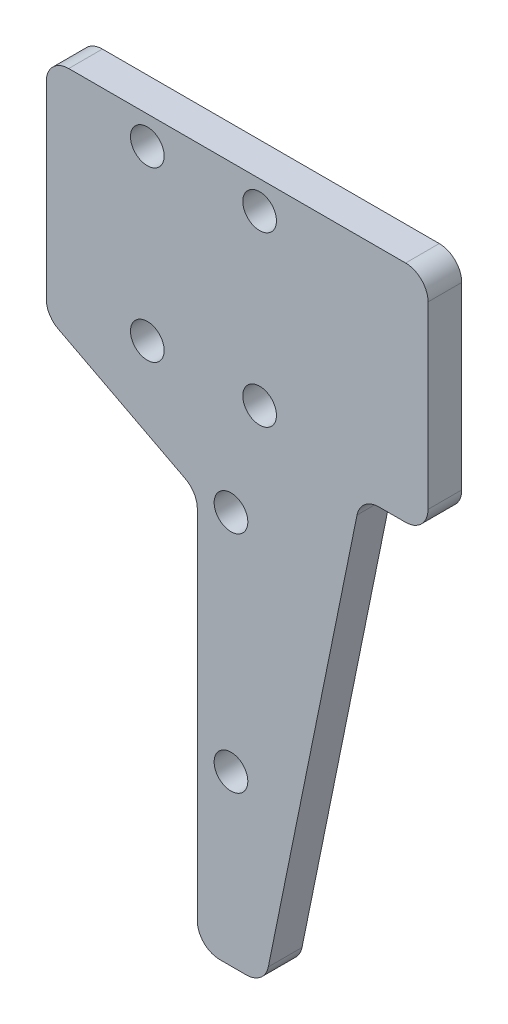
SolidWorks part; units mm, degrees
material "6061-T4 (SS)"
ref_plane "前视基准面" through (0, 0, 0) normal (0, 0, 1) x (1, 0, 0)
ref_plane "上视基准面" through (0, 0, 0) normal (0, 1, 0) x (1, 0, 0)
ref_plane "右视基准面" through (0, 0, 0) normal (1, 0, 0) x (0, 0, -1)
other "Configuration Table"
sketch "草图1" plane through (0, 0, 0) normal (0, 0, 1) x (1, 0, 0)
  line L0 (-14, -10) -> (-0.55, -17)
  line L1 (-5, -7.5) -> (5, -7.5) construction
  line L2 (-5, -7.5) -> (-5, 7.5) construction
  line L3 (-5, 7.5) -> (5, 7.5) construction
  line L4 (5, -7.5) -> (5, 7.5) construction
  line L5 (-5, -7.5) -> (5, 7.5) construction
  line L6 (-5, 7.5) -> (5, -7.5) construction
  line L7 (-14, -10) -> (14, -10)
  line L8 (-14, -10) -> (-14, 10)
  line L9 (-14, 10) -> (14, 10)
  line L10 (14, -10) -> (14, 10)
  line L11 (-14, -10) -> (14, 10) construction
  line L12 (-14, 10) -> (14, -10) construction
  line L13 (-0.55, -17) -> (5.45, -17)
  line L14 (-0.55, -17) -> (-0.55, -52)
  line L15 (-0.55, -52) -> (5.45, -52)
  line L16 (5.45, -17) -> (5.45, -52)
  line L17 (14, -10) -> (5.45, -52)
  circle A0 centre (5, 7.5) radius 1.5
  circle A1 centre (5, -7.5) radius 1.5
  circle A2 centre (-5, -7.5) radius 1.5
  circle A3 centre (-5, 7.5) radius 1.5
  point P0 (0, 0)
  point P6 (0, 0)
  dimension "D5" = 3
  dimension "D1" = 10
  dimension "D2" = 15
  dimension "D3" = 28
  dimension "D4" = 20
  dimension "D6" = 35
  dimension "D7" = 6
  dimension "D8" = 0.55
  dimension "D9" = 17
extrude "凸台-拉伸1" add sketch "草图1" along normal blind 3
sketch "草图4" plane through (0, 0, 3) normal (0, 0, 1) x (1, 0, 0)
  line L0 (2.45, -17) -> (2.45, -37) construction
  line L1 (2.45, -37) -> (2.45, -52) construction
  line L2 (-0.55, -52) -> (5.45, -52) construction
  line L3 (-0.55, -17) -> (-0.55, -52) construction
  circle A0 centre (2.45, -37) radius 1.5
  circle A1 centre (2.45, -17) radius 1.5
  dimension "D4" = 3
  dimension "D1" = 3
  dimension "D2" = 15
  dimension "D3" = 20
extrude "切除-拉伸1" cut sketch "草图4" against normal blind 3
sketch "草图6" plane through (0, 0, 3) normal (0, 0, 1) x (1, 0, 0)
  line L1 (14, -10) -> (20, -10)
  line L2 (14, -10) -> (14, 10)
  line L3 (14, 10) -> (20, 10)
  line L4 (20, -10) -> (20, 10)
  line L5 (-14, 10) -> (14, 10) construction
  dimension "D1" = 6
extrude "凸台-拉伸2" add sketch "草图6" against normal blind 3
fillet "圆角1" radius 2 8 edges at (-0.55, -52, 1.5) (-0.55, -17, 1.5) (-14, -10, 1.5) (-14, 10, 1.5) (20, 10, 1.5) (20, -10, 1.5) (5.45, -52, 1.5) (14, -10, 1.5)
